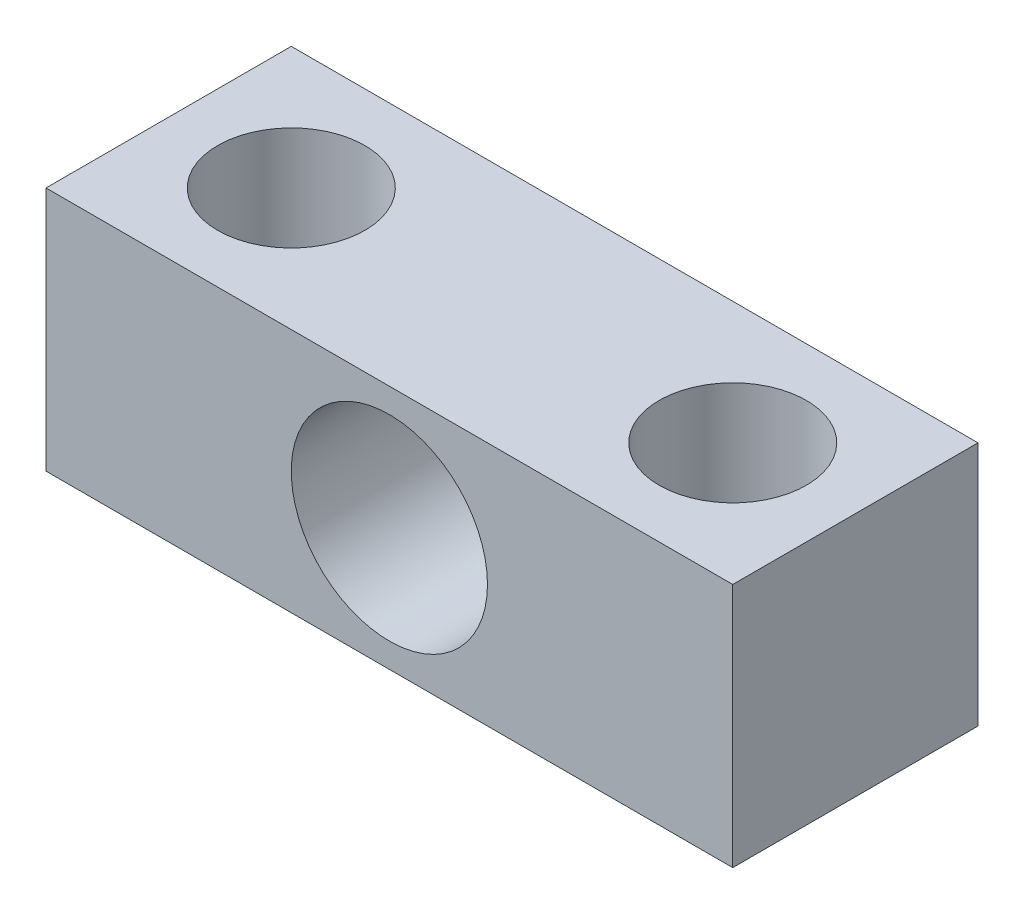
SolidWorks part; units mm, degrees
ref_plane "Plan de face" through (0, 0, 0) normal (0, 0, 1) x (1, 0, 0)
ref_plane "Plan de dessus" through (0, 0, 0) normal (0, 1, 0) x (1, 0, 0)
ref_plane "Plan de droite" through (0, 0, 0) normal (1, 0, 0) x (0, 0, -1)
sketch "Esquisse1" plane through (0, 0, 0) normal (0, 1, 0) x (1, 0, 0)
  line L1 (0, 0) -> (28, 0)
  line L2 (0, 0) -> (0, 10)
  line L3 (0, 10) -> (28, 10)
  line L4 (28, 0) -> (28, 10)
  dimension "D1" = 10
  dimension "D2" = 28
extrude "Extrusion1" add sketch "Esquisse1" along normal blind 10
sketch "Esquisse2" plane through (0, 0, 0) normal (0, 0, 1) x (1, 0, 0)
  line L0 (0, 10) -> (28, 10) construction
  line L1 (0, 10) -> (0, 0) construction
  circle A0 centre (14, 5) radius 4
  dimension "D1" = 8
  dimension "D2" = 5
  dimension "D3" = 14
extrude "Extrusion2" cut sketch "Esquisse2" against normal through all
sketch "Esquisse3" plane through (0, 10, 0) normal (0, 1, 0) x (1, 0, 0)
  line L0 (28, 10) -> (0, 10) construction
  line L1 (0, 10) -> (0, 0) construction
  line L2 (28, 0) -> (28, 10) construction
  circle A0 centre (5, 5) radius 3
  circle A1 centre (23, 5) radius 3
  dimension "D1" = 6
  dimension "D2" = 6
  dimension "D3" = 5
  dimension "D4" = 5
  dimension "D5" = 5
  dimension "D6" = 5
extrude "Extrusion3" cut sketch "Esquisse3" against normal through all
